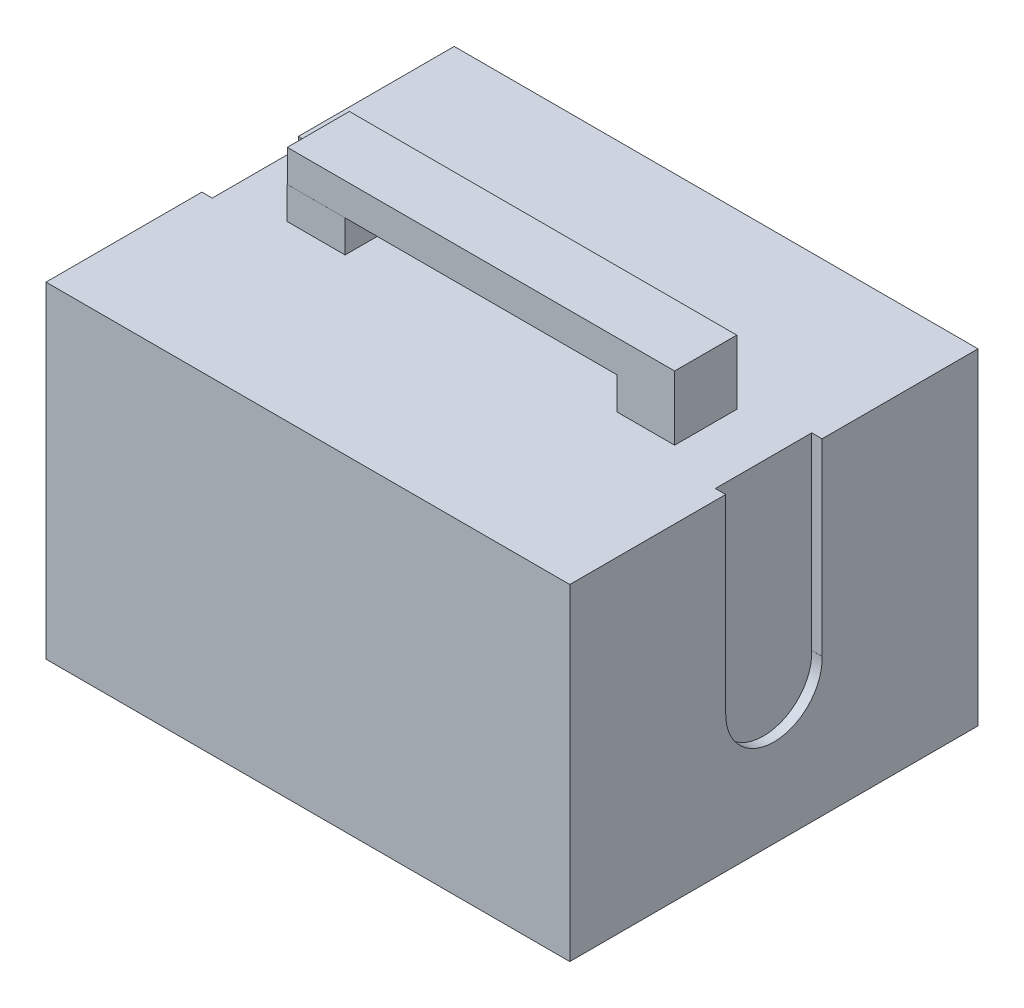
SolidWorks part; units mm, degrees
ref_plane "Front Plane" through (0, 0, 0) normal (0, 0, 1) x (1, 0, 0)
ref_plane "Top Plane" through (0, 0, 0) normal (0, 1, 0) x (1, 0, 0)
ref_plane "Right Plane" through (0, 0, 0) normal (1, 0, 0) x (0, 0, -1)
sketch "Sketch2" plane through (0, 0, 0) normal (0, 0, 1) x (1, 0, 0)
  line L1 (-81.4758, -50.8) -> (81.4758, -50.8)
  line L2 (-81.4758, -50.8) -> (-81.4758, 50.8)
  line L3 (-81.4758, 50.8) -> (81.4758, 50.8)
  line L4 (81.4758, -50.8) -> (81.4758, 50.8)
  line L5 (-81.4758, -50.8) -> (81.4758, 50.8) construction
  line L6 (-81.4758, 50.8) -> (81.4758, -50.8) construction
  line L7 (-71.1418, -44.45) -> (71.1418, -44.45)
  line L8 (-71.1418, -44.45) -> (-71.1418, 44.45)
  line L9 (-71.1418, 44.45) -> (71.1418, 44.45)
  line L10 (71.1418, -44.45) -> (71.1418, 44.45)
  line L11 (-71.1418, -44.45) -> (71.1418, 44.45) construction
  line L12 (-71.1418, 44.45) -> (71.1418, -44.45) construction
  point P0 (0, 0)
  point P6 (0, 0)
  point P11 (0, 0)
  dimension "D1" = 101.6
  dimension "D2" = 88.9
  dimension "D3" = 10.334
extrude "Boss-Extrude1" add sketch "Sketch2" along normal blind 127 contours L3 L4 L1 L2
sketch "Sketch6" plane through (0, 0, 0) normal (0, 0, 1) x (1, 0, 0)
  line L1 (-75.0362, -44.45) -> (75.0362, -44.45)
  line L2 (-75.0362, -44.45) -> (-75.0362, 44.45)
  line L3 (-75.0362, 44.45) -> (75.0362, 44.45)
  line L4 (75.0362, -44.45) -> (75.0362, 44.45)
  line L5 (-75.0362, -44.45) -> (75.0362, 44.45) construction
  line L6 (-75.0362, 44.45) -> (75.0362, -44.45) construction
  point P0 (0, 0)
  dimension "D1" = 88.9
extrude "Cut-Extrude1" cut sketch "Sketch6" along normal blind 114.3
sketch "Sketch8" plane through (0, 0, 0) normal (0, 0, 1) x (1, 0, 0)
  line L1 (75.0362, -44.45) -> (-75.0362, -44.45)
  line L2 (75.0362, -44.45) -> (75.0362, 44.45)
  line L3 (75.0362, 44.45) -> (-75.0362, 44.45)
  line L4 (-75.0362, -44.45) -> (-75.0362, 44.45)
  line L5 (75.0362, -44.45) -> (-75.0362, 44.45) construction
  line L6 (75.0362, 44.45) -> (-75.0362, -44.45) construction
  line L7 (29.648, -31.75) -> (-29.648, -31.75)
  line L8 (29.648, -31.75) -> (29.648, 31.75)
  line L9 (29.648, 31.75) -> (-29.648, 31.75)
  line L10 (-29.648, -31.75) -> (-29.648, 31.75)
  line L11 (29.648, -31.75) -> (-29.648, 31.75) construction
  line L12 (29.648, 31.75) -> (-29.648, -31.75) construction
  point P0 (0, 0)
  point P7 (0, 0)
  dimension "D1" = 63.5
sketch "Sketch9" plane through (-81.4758, 0, 0) normal (-1, 0, 0) x (0, 0, 1)
  line L0 (127, 50.8) -> (0, 50.8) construction
  line L1 (48.5026, 50.8) -> (78.5, 50.8)
  line L2 (48.5026, 50.8) -> (48.5026, -7.798)
  line L3 (48.5026, -7.798) -> (78.5, -7.798)
  line L4 (78.5, 50.8) -> (78.5, -7.798)
  line L5 (48.5026, 50.8) -> (78.5, -7.798) construction
  line L6 (48.5026, -7.798) -> (78.5, 50.8) construction
  line L11 (48.5026, -7.798) -> (78.5, -7.798)
  circle A0 centre (63.5013, -8.3866) radius 15
  point P4 (63.5013, 21.501)
  dimension "D3" = 30
  dimension "D1" = 29.9974
  dimension "D2" = 48.5
sketch "Sketch14" plane through (-81.4758, 0, 0) normal (-1, 0, 0) x (0, 0, 1)
  line L1 (48.5026, -7.798) -> (78.5, -7.798)
  line L2 (48.5026, -7.798) -> (48.5026, 50.8)
  line L3 (48.5026, 50.8) -> (78.5, 50.8)
  line L4 (78.5, -7.798) -> (78.5, 50.8)
  line L5 (48.5026, -7.798) -> (78.5, 50.8) construction
  line L6 (48.5026, 50.8) -> (78.5, -7.798) construction
  point P0 (63.5013, 21.501)
extrude "Cut-Extrude2" cut sketch "Sketch14" against normal blind 3.22
sketch "Sketch15" plane through (-81.4758, 0, 0) normal (-1, 0, 0) x (0, 0, 1)
  circle A0 centre (63.5013, -8.3866) radius 15
extrude "Cut-Extrude3" cut sketch "Sketch15" against normal blind 3.22
sketch "Sketch17" plane through (81.4758, 0, 0) normal (1, 0, 0) x (0, 0, -1)
  line L6 (-78.5, -7.798) -> (-48.5026, -7.798)
  line L8 (-78.5, -7.798) -> (-78.5, 50.8)
  line L9 (-78.5, 50.8) -> (-48.5026, 50.8)
  line L10 (-48.5026, -7.798) -> (-48.5026, 50.8)
  line L11 (-78.5, -7.798) -> (-48.5026, 50.8) construction
  line L12 (-78.5, 50.8) -> (-48.5026, -7.798) construction
  point P0 (-63.5013, 21.501)
extrude "Cut-Extrude4" cut sketch "Sketch17" against normal blind 3.22
sketch "Sketch18" plane through (81.4758, 0, 0) normal (1, 0, 0) x (0, 0, -1)
  circle A0 centre (-63.5013, -8.3866) radius 15
extrude "Cut-Extrude5" cut sketch "Sketch18" against normal blind 3.22
sketch "Sketch19" plane through (0, 50.8, 0) normal (0, 1, 0) x (1, 0, 0)
  line L1 (-60.2558, -53.8336) -> (-42.2558, -53.8336)
  line L2 (-60.2558, -53.8336) -> (-60.2558, -73.1664)
  line L3 (-60.2558, -73.1664) -> (-42.2558, -73.1664)
  line L4 (-42.2558, -53.8336) -> (-42.2558, -73.1664)
  line L5 (-60.2558, -53.8336) -> (-42.2558, -73.1664) construction
  line L6 (-60.2558, -73.1664) -> (-42.2558, -53.8336) construction
  line L7 (-66.88, 0) -> (66.88, 0) construction
  line L8 (42.2558, -53.83) -> (60.2558, -53.83)
  line L9 (42.2558, -53.83) -> (42.2558, -73.1629)
  line L10 (42.2558, -73.1629) -> (60.2558, -73.1629)
  line L11 (60.2558, -53.83) -> (60.2558, -73.1629)
  line L12 (-81.4758, 0) -> (81.4758, 0) construction
  line L13 (-78.2558, -78.5) -> (-78.2558, -48.5026) construction
  line L14 (78.2558, -48.5026) -> (78.2558, -78.5) construction
  point P0 (-51.2558, -63.5)
  dimension "D1" = 63.5
  dimension "D2" = 53.8336
  dimension "D3" = 53.83
  dimension "D4" = 18
  dimension "D5" = 18
  dimension "D6" = 18
  dimension "D7" = 18
extrude "Boss-Extrude2" add sketch "Sketch19" along normal blind 10
sketch "Sketch20" plane through (0, 60.8, 0) normal (0, 1, 0) x (1, 0, 0)
  line L1 (-60.2558, -53.8336) -> (60.2558, -53.8336)
  line L2 (-60.2558, -53.8336) -> (-60.2558, -73.1629)
  line L3 (-60.2558, -73.1629) -> (60.2558, -73.1629)
  line L4 (60.2558, -53.8336) -> (60.2558, -73.1629)
  line L5 (-60.2558, -53.8336) -> (60.2558, -73.1629) construction
  line L6 (-60.2558, -73.1629) -> (60.2558, -53.8336) construction
  point P4 (0, -63.4982)
extrude "Boss-Extrude3" add sketch "Sketch20" along normal blind 10
sketch "Sketch23" plane through (0, 0, 0) normal (0, 0, 1) x (1, 0, 0)
  line L0 (-81.4758, -50.8) -> (81.4758, 50.8) construction
  line L1 (39.2916, 24.4982) -> (-39.2916, 24.4982)
  line L2 (39.2916, 24.4982) -> (39.2916, -24.4982)
  line L3 (39.2916, -24.4982) -> (-39.2916, -24.4982)
  line L4 (-39.2916, 24.4982) -> (-39.2916, -24.4982)
  line L5 (39.2916, 24.4982) -> (-39.2916, -24.4982) construction
  line L6 (39.2916, -24.4982) -> (-39.2916, 24.4982) construction
  line L8 (75.0362, -44.45) -> (-75.0362, -44.45)
  line L9 (75.0362, -44.45) -> (75.0362, 44.45)
  line L10 (75.0362, 44.45) -> (-75.0362, 44.45)
  line L11 (-75.0362, -44.45) -> (-75.0362, 44.45)
  line L12 (75.0362, -44.45) -> (-75.0362, 44.45) construction
  line L13 (75.0362, 44.45) -> (-75.0362, -44.45) construction
  point P0 (0, 0)
  point P8 (0, 0)
sketch "Sketch28" plane through (0, 0, 0) normal (0, 0, 1) x (1, 0, 0)
  line L1 (75.0362, -44.45) -> (-75.0362, -44.45)
  line L2 (75.0362, -44.45) -> (75.0362, 44.45)
  line L3 (75.0362, 44.45) -> (-75.0362, 44.45)
  line L4 (-75.0362, -44.45) -> (-75.0362, 44.45)
  line L5 (75.0362, -44.45) -> (-75.0362, 44.45) construction
  line L6 (75.0362, 44.45) -> (-75.0362, -44.45) construction
  point P0 (0, 0)
extrude "Boss-Extrude5" add sketch "Sketch28" along normal blind 10.334
sketch "Sketch29" plane through (0, 0, 0) normal (0, 0, 1) x (1, 0, 0)
  line L1 (39.2916, -24.4982) -> (-39.2916, -24.4982)
  line L2 (39.2916, -24.4982) -> (39.2916, 24.4982)
  line L3 (39.2916, 24.4982) -> (-39.2916, 24.4982)
  line L4 (-39.2916, -24.4982) -> (-39.2916, 24.4982)
  line L5 (39.2916, -24.4982) -> (-39.2916, 24.4982) construction
  line L6 (39.2916, 24.4982) -> (-39.2916, -24.4982) construction
  point P0 (0, 0)
extrude "Cut-Extrude6" cut sketch "Sketch29" along normal blind 10.334
